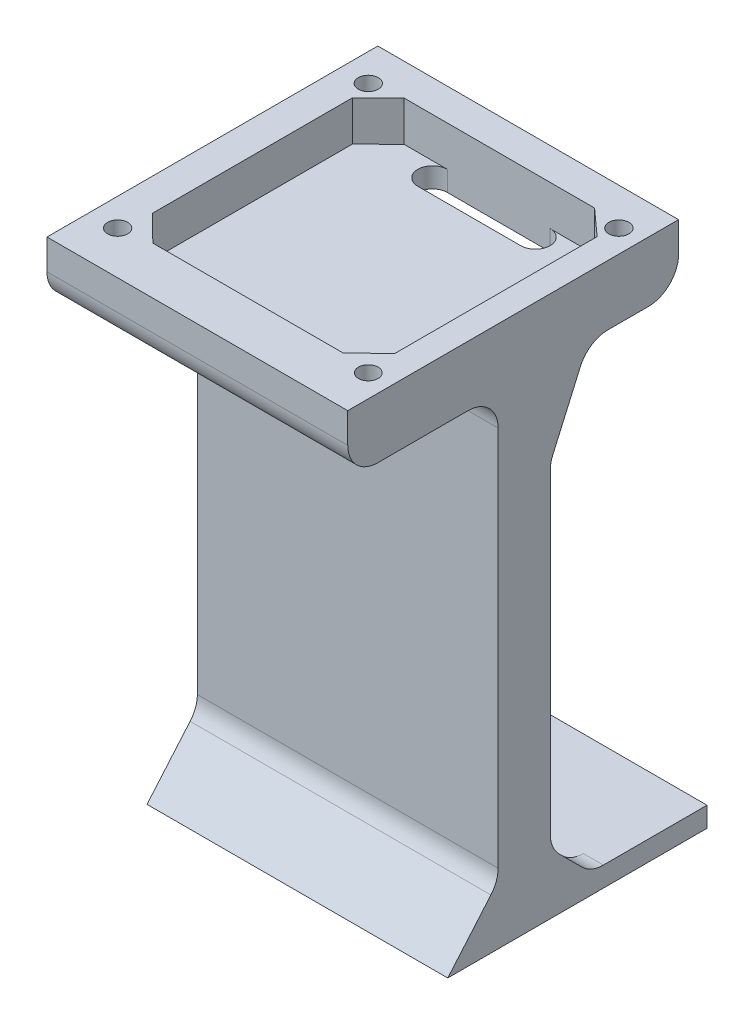
SolidWorks part; units mm, degrees
ref_plane "前视基准面" through (0, 0, 0) normal (0, 0, 1) x (1, 0, 0)
ref_plane "上视基准面" through (0, 0, 0) normal (0, 1, 0) x (1, 0, 0)
ref_plane "右视基准面" through (0, 0, 0) normal (1, 0, 0) x (0, 0, -1)
sketch "草图1" plane through (0, 0, 0) normal (0, 0, 1) x (1, 0, 0)
  line L0 (-15.7188, -20) -> (16.2812, -20) construction
  line L1 (-15.7188, 30) -> (14.2812, 30)
  line L2 (-15.7188, 30) -> (-15.7188, -20)
  line L3 (-15.7188, -20) -> (14.2812, -20)
  line L4 (14.2812, 30) -> (14.2812, -20)
  line L5 (-15.7188, -22) -> (-15.7188, -24) construction
  line L6 (14.2812, -24) -> (14.2812, -20) construction
  dimension "D1" = 50
extrude "凸台-拉伸1" add sketch "草图1" along normal blind 3
sketch "草图2" plane through (-15.7188, 0, 0) normal (-1, 0, 0) x (0, 0, 1)
  line L0 (0, -18.0036) -> (-17.8381, -18.0036)
  line L1 (0, 30) -> (0, -20) construction
  line L2 (-17.8381, -18.0036) -> (-17.8381, -20)
  line L3 (-201.8303, -20) -> (24.3932, -20) construction
  line L4 (-17.8381, -20) -> (8.023, -20)
  line L5 (8.023, -20) -> (3, -14.1341)
  line L6 (3, 30) -> (3, -20) construction
  line L7 (3, -14.1341) -> (0, -18.0036)
extrude "凸台-拉伸2" add sketch "草图2" against normal blind 30
sketch "草图3" plane through (0, 0, 3) normal (0, 0, 1) x (1, 0, 0)
  line L0 (13.3387, 34) -> (-14.1613, 34) construction
  line L1 (-15.7188, 30) -> (-12.5113, 30)
  line L2 (-15.7188, 30) -> (-15.7188, 34)
  line L3 (-15.7188, 34) -> (-12.5113, 34)
  line L4 (-12.5113, 30) -> (-12.5113, 34)
  line L5 (-12.5113, 30) -> (-12.5113, 34) construction
  line L6 (14.2812, 30) -> (11.6887, 30)
  line L7 (14.2812, 30) -> (14.2812, 34)
  line L8 (14.2812, 34) -> (11.6887, 34)
  line L9 (11.6887, 30) -> (11.6887, 34)
extrude "凸台-拉伸3" add sketch "草图3" against normal blind 18 and the other way blind 15
sketch "草图4" plane through (-15.7188, 0, 0) normal (-1, 0, 0) x (0, 0, 1)
  line L0 (18, 34) -> (18, 30) construction
  line L1 (-15, 30) -> (18, 30)
  line L2 (-15, 30) -> (-15, 28)
  line L3 (-15, 28) -> (18, 28)
  line L4 (18, 30) -> (18, 28)
  dimension "D1" = 2
extrude "凸台-拉伸4" add sketch "草图4" against normal up to surface (30 mm away) up to face at (14.2812, 8.8962, -1.423)
sketch "草图5" plane through (0, 30, 0) normal (0, 1, 0) x (1, 0, 0)
  line L0 (11.6887, -18) -> (-12.5113, -18)
  line L1 (-12.5113, -18) -> (-12.5113, -10.7001)
  line L2 (-12.5113, -18) -> (-12.5113, 15) construction
  line L3 (-12.4113, -10.7001) -> (-12.9113, -10.7001) construction
  line L4 (-12.5113, -10.7001) -> (-9.9113, -13.2501)
  line L5 (-9.9113, -13.2501) -> (9.0887, -13.2501)
  line L6 (9.0887, -13.2501) -> (11.6887, -10.7001)
  line L7 (11.6887, -10.7001) -> (9.0887, -13.2501) construction
  line L8 (12.0887, -10.7001) -> (11.5887, -10.7001) construction
  line L9 (11.6887, -10.7001) -> (11.6887, -18)
  line L10 (-12.5113, 15) -> (-12.5113, 9.2528)
  line L11 (-12.5113, 9.2528) -> (-9.9113, 11.8138)
  line L12 (-9.9113, 11.8138) -> (9.0887, 11.8138)
  line L13 (9.0887, 11.8138) -> (11.6887, 9.467)
  line L14 (11.6887, -18) -> (11.6887, 15) construction
  line L15 (11.6887, 9.467) -> (11.6887, 12.5499)
  line L16 (-14.1613, 12.5499) -> (13.3387, 12.5499) construction
  line L17 (11.6887, 12.5499) -> (11.6887, 15)
  line L18 (11.6887, 15) -> (-12.5113, 15)
extrude "凸台-拉伸5" add sketch "草图5" along normal up to surface (4 mm away) up to face at (-14.1151, 34, 1.5)
sketch "草图6" plane through (0, 30, 0) normal (0, 1, 0) x (1, 0, 0)
  line L0 (4.6541, 10.3454) -> (-5.6044, 10.3454) construction
  line L1 (4.6541, 8.877) -> (-5.6044, 8.877)
  line L2 (4.6541, 11.8138) -> (-5.6044, 11.8138)
  line L3 (-9.9113, 11.8138) -> (9.0887, 11.8138) construction
  arc A0 (4.6541, 8.877) -> (4.6541, 11.8138) centre (4.6541, 10.3454) ccw
  arc A1 (-5.6044, 11.8138) -> (-5.6044, 8.877) centre (-5.6044, 10.3454) ccw
  point P2 (-0.4751, 10.3454)
extrude "切除-拉伸1" cut sketch "草图6" against normal blind 5
sketch "草图7" plane through (0, 34, 0) normal (0, 1, 0) x (1, 0, 0)
  circle A0 centre (-12.9634, -13.708) radius 1
  circle A1 centre (12.0366, -13.708) radius 0.9837
  circle A2 centre (12.0366, 11.292) radius 1
  circle A3 centre (-12.9634, 11.292) radius 1
extrude "切除-拉伸2" cut sketch "草图7" against normal blind 5
fillet "圆角1" radius 3 2 edges at (-0.7188, 28, 18) (-0.7188, 28, -15)
fillet "圆角2" radius 3 1 edges at (-0.7188, 28, 3)
sketch "草图11" plane through (14.2812, 0, 0) normal (1, 0, 0) x (0, 0, -1)
  line L8 (6, 28) -> (2.2057, 19.3826)
  line L9 (0, 28) -> (12, 28) construction
  line L10 (2.2057, 19.3826) -> (2.2057, -13.9549)
  line L11 (2.2057, -13.9549) -> (6.2544, -18.0036)
  line L12 (0, -18.0036) -> (17.8381, -18.0036) construction
  line L13 (6.2544, -18.0036) -> (0, -18.0036)
  line L14 (0, -18.0036) -> (0, 28)
  line L15 (0, 28) -> (6, 28)
extrude "凸台-拉伸6" add sketch "草图11" against normal blind 2
fillet "圆角3" radius 3 4 edges at (13.2812, -18.0036, -6.2544) (13.2812, -13.9549, -2.2057) (13.2812, 19.3826, -2.2057) (13.2812, 28, -6)
fillet "圆角4" radius 3 1 edges at (-0.7188, -14.1341, 3)
